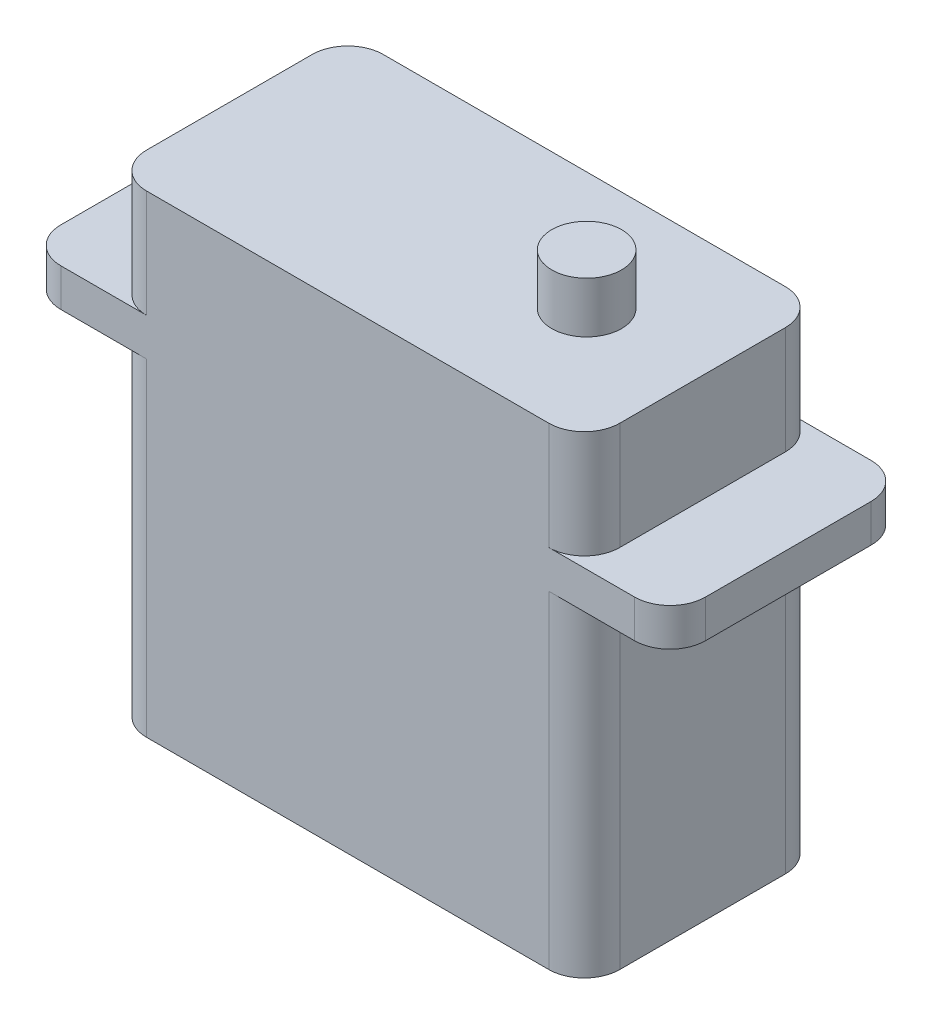
SolidWorks part; units mm, degrees
ref_plane "Front Plane" through (0, 0, 0) normal (0, 0, 1) x (1, 0, 0)
ref_plane "Top Plane" through (0, 0, 0) normal (0, 1, 0) x (1, 0, 0)
ref_plane "Right Plane" through (0, 0, 0) normal (1, 0, 0) x (0, 0, -1)
sketch "Sketch1" plane through (0, 0, 0) normal (0, 1, 0) x (1, 0, 0)
  line L1 (-20, -10) -> (20, -10)
  line L2 (-20, -10) -> (-20, 10)
  line L3 (-20, 10) -> (20, 10)
  line L4 (20, -10) -> (20, 10)
  line L5 (-20, -10) -> (20, 10) construction
  line L6 (-20, 10) -> (20, -10) construction
  point P0 (0, 0)
  dimension "D1" = 40
  dimension "D2" = 20
extrude "Boss-Extrude1" add sketch "Sketch1" along normal blind 40
sketch "Sketch2" plane through (0, 0, 10) normal (0, 0, 1) x (1, 0, 0)
  line L0 (-20, 0) -> (20, 0) construction
  line L1 (-27.25, 27.7) -> (27.25, 27.7)
  line L2 (-27.25, 27.7) -> (-27.25, 30.9)
  line L3 (-27.25, 30.9) -> (27.25, 30.9)
  line L4 (27.25, 27.7) -> (27.25, 30.9)
  point P6 (0, 27.7)
  dimension "D1" = 27.7
  dimension "D2" = 54.5
  dimension "D3" = 3.2
extrude "Boss-Extrude2" add sketch "Sketch2" against normal up to surface (20 mm away) contours L3 L4 L1 L2 up to face at (0, 20, -10)
fillet "Fillet1" radius 3 12 edges at (20, 13.85, -10) (20, 13.85, 10) (27.25, 29.3, -10) (27.25, 29.3, 10) (20, 35.45, -10) (20, 35.45, 10) (-27.25, 29.3, -10) (-27.25, 29.3, 10) (-20, 35.45, -10) (-20, 13.85, -10) (-20, 13.85, 10) (-20, 35.45, 10)
sketch "Sketch3" plane through (0, 40, 0) normal (0, 1, 0) x (1, 0, 0)
  line L0 (20, -7) -> (20, 7) construction
  circle A0 centre (10.2, 0) radius 2.95
  dimension "D2" = 5.9
  dimension "D1" = 9.8
extrude "Boss-Extrude3" add sketch "Sketch3" along normal blind 4.3
sketch "Sketch4" plane through (0, 0, 10) normal (0, 0, 1) x (1, 0, 0)
  line L0 (-17, 27.7) -> (17, 27.7) construction
  text T0 "<b>BETU 25kg</b>\r\n" font "Century Gothic" height 3.175
